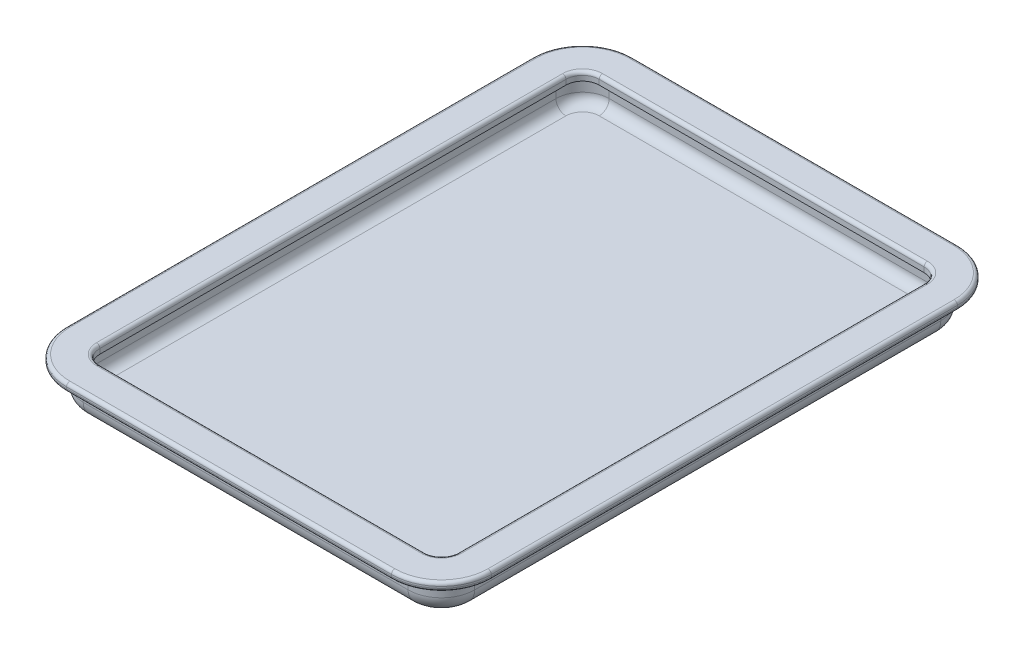
SolidWorks part; units mm, degrees
ref_plane "Front Plane" through (0, 0, 0) normal (0, 0, 1) x (1, 0, 0)
ref_plane "Top Plane" through (0, 0, 0) normal (0, 1, 0) x (1, 0, 0)
ref_plane "Right Plane" through (0, 0, 0) normal (1, 0, 0) x (0, 0, -1)
sketch "Sketch1" plane through (0, 0, 0) normal (0, 1, 0) x (1, 0, 0)
  line L1 (-74.676, -101.6) -> (74.676, -101.6)
  line L2 (-74.676, -101.6) -> (-74.676, 101.6)
  line L3 (-74.676, 101.6) -> (74.676, 101.6)
  line L4 (74.676, -101.6) -> (74.676, 101.6)
  line L5 (-74.676, -101.6) -> (74.676, 101.6) construction
  line L6 (-74.676, 101.6) -> (74.676, -101.6) construction
  point P0 (0, 0)
  dimension "D1" = 203.2
  dimension "D2" = 149.352
extrude "Boss-Extrude1" add sketch "Sketch1" along normal blind 12.7
fillet "Fillet1" radius 12.7 4 edges at (-74.676, 6.35, -101.6) (-74.676, 6.35, 101.6) (74.676, 6.35, -101.6) (74.676, 6.35, 101.6)
fillet "Fillet3" radius 6.35 8 edges at (-70.9563, 0, 97.8803) (0, 0, 101.6) (70.9563, 0, 97.8803) (74.676, 0, 0) (70.9563, 0, -97.8803) (0, 0, -101.6) (-70.9563, 0, -97.8803) (-74.676, 0, 0)
shell "Shell1" thickness 2.54
sketch "Sketch2" plane through (0, 12.7, 0) normal (0, 1, 0) x (1, 0, 0)
  line L20 (-61.976, -101.6) -> (61.976, -101.6) construction
  line L21 (74.676, -88.9) -> (74.676, 88.9) construction
  line L22 (61.976, 101.6) -> (-61.976, 101.6) construction
  line L23 (-74.676, 88.9) -> (-74.676, -88.9) construction
  line L24 (-68.326, -88.9) -> (-68.326, 88.9) construction
  line L25 (61.976, -95.25) -> (-61.976, -95.25) construction
  line L26 (68.326, 88.9) -> (68.326, -88.9) construction
  line L27 (-61.976, 95.25) -> (61.976, 95.25) construction
  line L28 (-61.976, -101.6) -> (61.976, -101.6) construction
  line L29 (74.676, -88.9) -> (74.676, 88.9) construction
  line L30 (61.976, 101.6) -> (-61.976, 101.6) construction
  line L31 (-74.676, 88.9) -> (-74.676, -88.9) construction
  line L32 (-68.326, -88.9) -> (-68.326, 88.9)
  line L33 (61.976, -95.25) -> (-61.976, -95.25)
  line L34 (68.326, 88.9) -> (68.326, -88.9)
  line L35 (-61.976, 95.25) -> (61.976, 95.25)
  line L36 (61.976, 107.95) -> (-61.976, 107.95)
  line L37 (-81.026, 88.9) -> (-81.026, -88.9)
  line L38 (-61.976, -107.95) -> (61.976, -107.95)
  line L39 (81.026, -88.9) -> (81.026, 88.9)
  arc A20 (-74.676, -88.9) -> (-61.976, -101.6) centre (-61.976, -88.9) ccw construction
  arc A21 (61.976, -101.6) -> (74.676, -88.9) centre (61.976, -88.9) ccw construction
  arc A22 (74.676, 88.9) -> (61.976, 101.6) centre (61.976, 88.9) ccw construction
  arc A23 (-61.976, 101.6) -> (-74.676, 88.9) centre (-61.976, 88.9) ccw construction
  arc A24 (-68.326, -88.9) -> (-61.976, -95.25) centre (-61.976, -88.9) ccw construction
  arc A25 (61.976, -95.25) -> (68.326, -88.9) centre (61.976, -88.9) ccw construction
  arc A26 (68.326, 88.9) -> (61.976, 95.25) centre (61.976, 88.9) ccw construction
  arc A27 (-61.976, 95.25) -> (-68.326, 88.9) centre (-61.976, 88.9) ccw construction
  arc A28 (-74.676, -88.9) -> (-61.976, -101.6) centre (-61.976, -88.9) ccw construction
  arc A29 (61.976, -101.6) -> (74.676, -88.9) centre (61.976, -88.9) ccw construction
  arc A30 (74.676, 88.9) -> (61.976, 101.6) centre (61.976, 88.9) ccw construction
  arc A31 (-61.976, 101.6) -> (-74.676, 88.9) centre (-61.976, 88.9) ccw construction
  arc A32 (-68.326, -88.9) -> (-61.976, -95.25) centre (-61.976, -88.9) ccw
  arc A33 (61.976, -95.25) -> (68.326, -88.9) centre (61.976, -88.9) ccw
  arc A34 (68.326, 88.9) -> (61.976, 95.25) centre (61.976, 88.9) ccw
  arc A35 (-61.976, 95.25) -> (-68.326, 88.9) centre (-61.976, 88.9) ccw
  arc A36 (-61.976, 107.95) -> (-81.026, 88.9) centre (-61.976, 88.9) ccw
  arc A37 (-81.026, -88.9) -> (-61.976, -107.95) centre (-61.976, -88.9) ccw
  arc A38 (61.976, -107.95) -> (81.026, -88.9) centre (61.976, -88.9) ccw
  arc A39 (81.026, 88.9) -> (61.976, 107.95) centre (61.976, 88.9) ccw
  dimension "D1" = 6.35
extrude "Boss-Extrude2" add sketch "Sketch2" along normal blind 3.175
fillet "Fillet2" radius 1.27 24 edges at (0, 12.7, -107.95) (75.4464, 12.7, -102.3704) (81.026, 12.7, 0) (75.4464, 12.7, 102.3704) (0, 12.7, 107.95) (-75.4464, 12.7, 102.3704) (-81.026, 12.7, 0) (66.4661, 15.875, 93.3901) (68.326, 15.875, 0) (66.4661, 15.875, -93.3901) (0, 15.875, -95.25) (-66.4661, 15.875, -93.3901) (-68.326, 15.875, 0) (-66.4661, 15.875, 93.3901) (0, 15.875, 95.25) (81.026, 15.875, 0) (75.4464, 15.875, 102.3704) (0, 15.875, 107.95) (-75.4464, 15.875, 102.3704) (-81.026, 15.875, 0) (-75.4464, 15.875, -102.3704) (0, 15.875, -107.95) (75.4464, 15.875, -102.3704) (-75.4464, 12.7, -102.3704)
